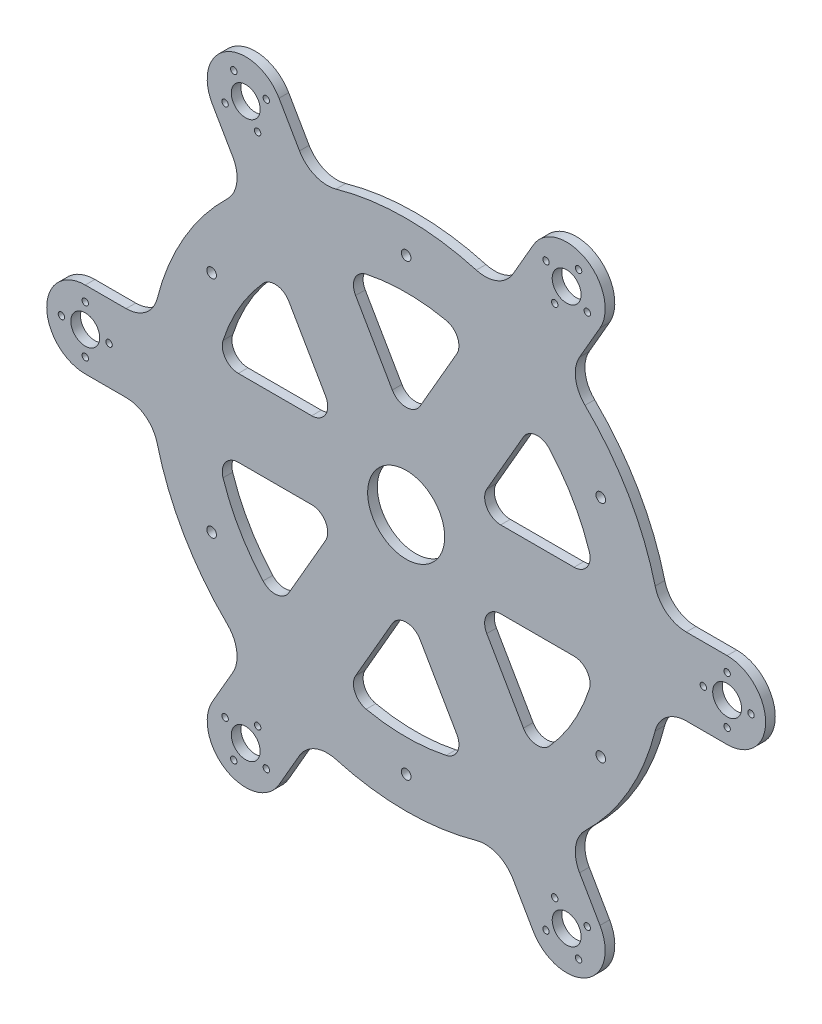
SolidWorks part; units mm, degrees
ref_plane "Front Plane" through (0, 0, 0) normal (0, 0, 1) x (1, 0, 0)
ref_plane "Top Plane" through (0, 0, 0) normal (0, 1, 0) x (1, 0, 0)
ref_plane "Right Plane" through (0, 0, 0) normal (1, 0, 0) x (0, 0, -1)
sketch "Sketch1" plane through (0, 0, 0) normal (0, 0, 1) x (1, 0, 0)
  line L0 (-561.3531, -948.2921) -> (24438.6469, 42352.9781) construction
  line L1 (-540.4731, -960.1269) -> (24459.5269, 42341.1433) construction
  line L2 (460.2716, -773.2137) -> (-24539.7284, 42528.0564) construction
  line L3 (439.0754, -784.5009) -> (-24560.9246, 42516.7693) construction
  line L4 (898.9248, 12) -> (-49101.0752, 12) construction
  line L5 (900.72, -12) -> (-49099.28, -12) construction
  line L6 (-54.0272, 69.5778) -> (-60.3923, 80.6025)
  line L7 (-33.2425, 81.5778) -> (-39.6077, 92.6025)
  line L8 (33.2425, 81.5778) -> (39.6077, 92.6025)
  line L9 (54.0272, 69.5778) -> (60.3923, 80.6025)
  line L10 (87.2697, 12) -> (100, 12)
  line L11 (87.2697, -12) -> (100, -12)
  line L12 (54.0272, -69.5778) -> (60.3923, -80.6025)
  line L13 (33.2425, -81.5778) -> (39.6077, -92.6025)
  line L14 (-54.0272, -69.5778) -> (-60.3923, -80.6025)
  line L15 (-33.2425, -81.5778) -> (-39.6077, -92.6025)
  line L16 (-87.2697, 12) -> (-100, 12)
  line L17 (-87.2697, -12) -> (-100, -12)
  line L18 (-36.5457, 39.299) -> (-25.1147, 19.5)
  line L19 (-29.4449, 12) -> (-52.3068, 12)
  line L20 (15.7611, 51.299) -> (4.3301, 31.5)
  line L21 (-4.3301, 31.5) -> (-15.7611, 51.299)
  line L22 (36.5457, 39.299) -> (25.1147, 19.5)
  line L23 (29.4449, 12) -> (52.3068, 12)
  line L24 (52.3068, -12) -> (29.4449, -12)
  line L25 (25.1147, -19.5) -> (36.5457, -39.299)
  line L26 (15.7611, -51.299) -> (4.3301, -31.5)
  line L27 (-4.3301, -31.5) -> (-15.7611, -51.299)
  line L28 (-36.5457, -39.299) -> (-25.1147, -19.5)
  line L29 (-29.4449, -12) -> (-52.3068, -12)
  circle A0 centre (0, 0) radius 100 construction
  circle A1 centre (100, 0) radius 4.5
  circle A2 centre (100, 0) radius 7.425 construction
  circle A3 centre (107.425, 0) radius 1
  circle A4 centre (100, 7.425) radius 1
  circle A5 centre (92.575, 0) radius 1
  circle A6 centre (100, -7.425) radius 1
  arc A7 (100, -12) -> (100, 12) centre (100, 0) ccw
  circle A8 centre (50, -86.6025) radius 4.5
  circle A9 centre (56.4302, -82.89) radius 1
  circle A10 centre (53.7125, -93.0328) radius 1
  circle A11 centre (43.5698, -90.315) radius 1
  circle A12 centre (46.2875, -80.1723) radius 1
  circle A13 centre (50, -86.6025) radius 7.425 construction
  arc A14 (39.6077, -92.6025) -> (60.3923, -80.6025) centre (50, -86.6025) ccw
  circle A15 centre (-50, -86.6025) radius 4.5
  circle A16 centre (-43.5698, -90.315) radius 1
  circle A17 centre (-53.7125, -93.0328) radius 1
  circle A18 centre (-56.4302, -82.89) radius 1
  circle A19 centre (-46.2875, -80.1723) radius 1
  circle A20 centre (-50, -86.6025) radius 7.425 construction
  arc A21 (-60.3923, -80.6025) -> (-39.6077, -92.6025) centre (-50, -86.6025) ccw
  circle A22 centre (-100, 0) radius 4.5
  circle A23 centre (-100, -7.425) radius 1
  circle A24 centre (-107.425, 0) radius 1
  circle A25 centre (-100, 7.425) radius 1
  circle A26 centre (-92.575, 0) radius 1
  circle A27 centre (-100, 0) radius 7.425 construction
  arc A28 (-100, 12) -> (-100, -12) centre (-100, 0) ccw
  circle A29 centre (-50, 86.6025) radius 4.5
  circle A30 centre (-56.4302, 82.89) radius 1
  circle A31 centre (-53.7125, 93.0328) radius 1
  circle A32 centre (-43.5698, 90.315) radius 1
  circle A33 centre (-46.2875, 80.1723) radius 1
  circle A34 centre (-50, 86.6025) radius 7.425 construction
  arc A35 (-39.6077, 92.6025) -> (-60.3923, 80.6025) centre (-50, 86.6025) ccw
  circle A36 centre (50, 86.6025) radius 4.5
  circle A37 centre (43.5698, 90.315) radius 1
  circle A38 centre (53.7125, 93.0328) radius 1
  circle A39 centre (56.4302, 82.89) radius 1
  circle A40 centre (46.2875, 80.1723) radius 1
  circle A41 centre (50, 86.6025) radius 7.425 construction
  arc A42 (60.3923, 80.6025) -> (39.6077, 92.6025) centre (50, 86.6025) ccw
  arc A43 (-55.7221, 57.4025) -> (-77.5731, 19.5556) centre (0, 0) ccw
  circle A44 centre (0, 0) radius 70 construction
  arc A45 (-57.0619, -18.5455) -> (-44.5918, -40.1444) centre (0, 0) ccw
  circle A46 centre (0, 0) radius 12
  arc A47 (-44.5918, 40.1444) -> (-57.0619, 18.5455) centre (0, 0) ccw
  arc A48 (12.4701, 58.6898) -> (-12.4701, 58.6898) centre (0, 0) ccw
  arc A49 (57.0619, 18.5455) -> (44.5918, 40.1444) centre (0, 0) ccw
  arc A50 (44.5918, -40.1444) -> (57.0619, -18.5455) centre (0, 0) ccw
  arc A51 (-12.4701, -58.6898) -> (12.4701, -58.6898) centre (0, 0) ccw
  arc A52 (-21.8509, -76.958) -> (21.8509, -76.958) centre (0, 0) ccw
  arc A53 (55.7221, -57.4025) -> (77.5731, -19.5556) centre (0, 0) ccw
  arc A54 (21.8509, 76.958) -> (-21.8509, 76.958) centre (0, 0) ccw
  arc A55 (-77.5731, -19.5556) -> (-55.7221, -57.4025) centre (0, 0) ccw
  arc A56 (77.5731, 19.5556) -> (55.7221, 57.4025) centre (0, 0) ccw
  circle A57 centre (0, 70) radius 1.5
  circle A58 centre (60.6218, 35) radius 1.5
  circle A59 centre (60.6218, -35) radius 1.5
  circle A60 centre (0, -70) radius 1.5
  circle A61 centre (-60.6218, -35) radius 1.5
  circle A62 centre (-60.6218, 35) radius 1.5
  arc A63 (-25.1147, -19.5) -> (-29.4449, -12) centre (-29.4449, -17) ccw
  arc A64 (-52.3068, -12) -> (-57.0619, -18.5455) centre (-52.3068, -17) ccw
  arc A65 (-44.5918, -40.1444) -> (-36.5457, -39.299) centre (-40.8758, -36.799) ccw
  arc A66 (4.3301, -31.5) -> (-4.3301, -31.5) centre (0, -34) ccw
  arc A67 (-15.7611, -51.299) -> (-12.4701, -58.6898) centre (-11.431, -53.799) ccw
  arc A68 (12.4701, -58.6898) -> (15.7611, -51.299) centre (11.431, -53.799) ccw
  arc A69 (29.4449, -12) -> (25.1147, -19.5) centre (29.4449, -17) ccw
  arc A70 (36.5457, -39.299) -> (44.5918, -40.1444) centre (40.8758, -36.799) ccw
  arc A71 (57.0619, -18.5455) -> (52.3068, -12) centre (52.3068, -17) ccw
  arc A72 (25.1147, 19.5) -> (29.4449, 12) centre (29.4449, 17) ccw
  arc A73 (52.3068, 12) -> (57.0619, 18.5455) centre (52.3068, 17) ccw
  arc A74 (44.5918, 40.1444) -> (36.5457, 39.299) centre (40.8758, 36.799) ccw
  arc A75 (4.3301, 31.5) -> (-4.3301, 31.5) centre (0, 34) cw
  arc A76 (15.7611, 51.299) -> (12.4701, 58.6898) centre (11.431, 53.799) ccw
  arc A77 (-12.4701, 58.6898) -> (-15.7611, 51.299) centre (-11.431, 53.799) ccw
  arc A78 (-57.0619, 18.5455) -> (-52.3068, 12) centre (-52.3068, 17) ccw
  arc A79 (-29.4449, 12) -> (-25.1147, 19.5) centre (-29.4449, 17) ccw
  arc A80 (-36.5457, 39.299) -> (-44.5918, 40.1444) centre (-40.8758, 36.799) ccw
  arc A81 (77.5731, 19.5556) -> (87.2697, 12) centre (87.2697, 22) ccw
  arc A82 (87.2697, -12) -> (77.5731, -19.5556) centre (87.2697, -22) ccw
  arc A83 (55.7221, -57.4025) -> (54.0272, -69.5778) centre (62.6874, -64.5778) ccw
  arc A84 (33.2425, -81.5778) -> (21.8509, -76.958) centre (24.5823, -86.5778) ccw
  arc A85 (-21.8509, -76.958) -> (-33.2425, -81.5778) centre (-24.5823, -86.5778) ccw
  arc A86 (-54.0272, -69.5778) -> (-55.7221, -57.4025) centre (-62.6874, -64.5778) ccw
  arc A87 (-77.5731, -19.5556) -> (-87.2697, -12) centre (-87.2697, -22) ccw
  arc A88 (-87.2697, 12) -> (-77.5731, 19.5556) centre (-87.2697, 22) ccw
  arc A89 (-54.0272, 69.5778) -> (-55.7221, 57.4025) centre (-62.6874, 64.5778) cw
  arc A90 (55.7221, 57.4025) -> (54.0272, 69.5778) centre (62.6874, 64.5778) cw
  arc A91 (33.2425, 81.5778) -> (21.8509, 76.958) centre (24.5823, 86.5778) cw
  arc A92 (-21.8509, 76.958) -> (-33.2425, 81.5778) centre (-24.5823, 86.5778) cw
  point P77 (0, 0)
  point P152 (0, 0)
  point P153 (-20.7846, -12)
  point P156 (-58.7878, -12)
  point P159 (-39.7862, -44.9117)
  point P162 (0, -24)
  point P165 (-19.0016, -56.9117)
  point P168 (19.0016, -56.9117)
  point P171 (20.7846, -12)
  point P174 (39.7862, -44.9117)
  point P177 (58.7878, -12)
  point P180 (20.7846, 12)
  point P183 (58.7878, 12)
  point P186 (39.7862, 44.9117)
  point P189 (0, 24)
  point P192 (19.0016, 56.9117)
  point P195 (-19.0016, 56.9117)
  point P198 (-58.7878, 12)
  point P201 (-20.7846, 12)
  point P204 (-39.7862, 44.9117)
  point P207 (79.0949, 12)
  point P210 (79.0949, -12)
  point P213 (49.9397, -62.4982)
  point P216 (29.1551, -74.4982)
  point P219 (-29.1551, -74.4982)
  point P222 (-49.9397, -62.4982)
  point P225 (-79.0949, -12)
  point P228 (-79.0949, 12)
  point P231 (-49.9397, 62.4982)
  point P233 (49.9397, 62.4982)
  point P236 (29.1551, 74.4982)
  point P239 (-29.1551, 74.4982)
  dimension "D1" = 6
  dimension "D2" = 5
  dimension "D3" = 9
  dimension "D4" = 14.85
  dimension "D5" = 2
  dimension "D6" = 2
  dimension "D7" = 2
  dimension "D8" = 2
  dimension "D9" = 12
  dimension "D10" = 80
  dimension "D11" = 140
  dimension "D12" = 60
  dimension "D14" = 3
  dimension "D15" = 10
  dimension "D16" = 10
  dimension "D17" = 200
  dimension "D18" = 22.8619
  dimension "D20" = 70
  dimension "D19" = 22.8619
  dimension "D21" = 70
  dimension "D13" = 6
extrude "Boss-Extrude1" add sketch "Sketch1" along normal blind 3
